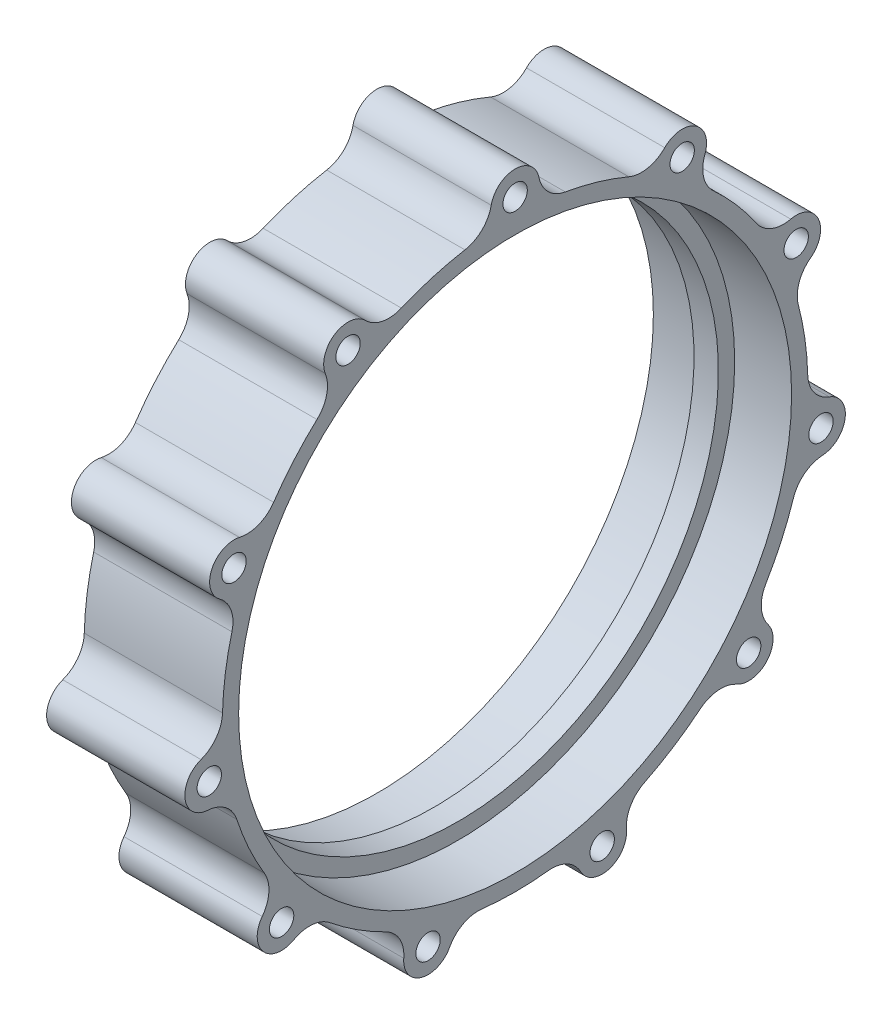
SolidWorks part; units mm, degrees
material "6061 合金"
ref_plane "前视基准面" through (0, 0, 0) normal (0, 0, 1) x (1, 0, 0)
ref_plane "上视基准面" through (0, 0, 0) normal (0, 1, 0) x (1, 0, 0)
ref_plane "右视基准面" through (0, 0, 0) normal (1, 0, 0) x (0, 0, -1)
sketch "草图1" plane through (0, 0, 0) normal (0, 1, 0) x (1, 0, 0)
  line L0 (0, 0) -> (24.0184, 0) construction
  line L1 (0, 34) -> (7, 34)
  line L2 (7, 34) -> (7, 32)
  line L3 (7, 32) -> (10, 32)
  line L4 (10, 32) -> (10, 34)
  line L5 (10, 34) -> (17, 34)
  line L6 (17, 34) -> (17, 36)
  line L7 (17, 36) -> (0, 36)
  line L8 (0, 36) -> (0, 34)
  dimension "D1" = 3
  dimension "D2" = 2
  dimension "D3" = 7
  dimension "D4" = 34
  dimension "D5" = 2
revolve "旋转1" add sketch "草图1" angle 360 about L0
sketch "草图2" plane through (17, 0, 0) normal (1, 0, 0) x (0, 0, -1)
  line L0 (0, 0) -> (0, 38) construction
  arc A1 (2.1754, 35.9342) -> (-2.1754, 35.9342) centre (0, 38) ccw
  circle A2 centre (0, 0) radius 36 construction
  arc A3 (2.1754, 35.9342) -> (-2.1754, 35.9342) centre (0, 0) ccw
  arc A4 (21.2576, 29.0537) -> (17.5974, 31.4059) centre (0, 0) ccw
  arc A5 (21.2576, 29.0537) -> (17.5974, 31.4059) centre (20.5444, 31.9676) ccw
  arc A7 (33.5906, 12.9488) -> (31.7832, 16.9065) centre (0, 0) ccw
  arc A8 (33.5906, 12.9488) -> (31.7832, 16.9065) centre (34.566, 15.7858) ccw
  arc A10 (35.2589, -7.2673) -> (35.878, -2.9607) centre (0, 0) ccw
  arc A11 (35.2589, -7.2673) -> (35.878, -2.9607) centre (37.6132, -5.408) ccw
  arc A13 (25.7327, -25.176) -> (28.5819, -21.8878) centre (0, 0) ccw
  arc A14 (25.7327, -25.176) -> (28.5819, -21.8878) centre (28.7185, -24.8847) ccw
  arc A16 (8.0365, -35.0915) -> (12.2112, -33.8657) centre (0, 0) ccw
  arc A17 (8.0365, -35.0915) -> (12.2112, -33.8657) centre (10.7058, -36.4607) ccw
  arc A18 (-12.2112, -33.8657) -> (-8.0365, -35.0915) centre (0, 0) ccw
  arc A19 (-12.2112, -33.8657) -> (-8.0365, -35.0915) centre (-10.7058, -36.4607) ccw
  arc A20 (-28.5819, -21.8878) -> (-25.7327, -25.176) centre (0, 0) ccw
  arc A21 (-28.5819, -21.8878) -> (-25.7327, -25.176) centre (-28.7185, -24.8847) ccw
  arc A22 (-35.878, -2.9607) -> (-35.2589, -7.2673) centre (0, 0) ccw
  arc A23 (-35.878, -2.9607) -> (-35.2589, -7.2673) centre (-37.6132, -5.408) ccw
  arc A24 (-31.7832, 16.9065) -> (-33.5906, 12.9488) centre (0, 0) ccw
  arc A25 (-31.7832, 16.9065) -> (-33.5906, 12.9488) centre (-34.566, 15.7858) ccw
  arc A26 (-17.5974, 31.4059) -> (-21.2576, 29.0537) centre (0, 0) ccw
  arc A27 (-17.5974, 31.4059) -> (-21.2576, 29.0537) centre (-20.5444, 31.9676) ccw
  point P30 (0, 0)
  dimension "D3" = 6
  dimension "D2" = 38
  dimension "D4" = 11
extrude "凸台-拉伸1" add sketch "草图2" against normal up to surface (17 mm away) up to face at (0, 0, 34)
fillet "圆角1" radius 4 22 edges at (8.5, 35.9342, 2.1754) (8.5, 35.9342, -2.1754) (8.5, -33.8657, -12.2112) (8.5, -35.0915, -8.0365) (8.5, -21.8878, -28.5819) (8.5, -25.176, -25.7327) (8.5, -2.9607, -35.878) (8.5, -7.2673, -35.2589) (8.5, 16.9065, -31.7832) (8.5, 12.9488, -33.5906) (8.5, 31.4059, -17.5974) (8.5, 29.0537, -21.2576) (8.5, 29.0537, 21.2576) (8.5, 31.4059, 17.5974) (8.5, 12.9488, 33.5906) (8.5, 16.9065, 31.7832) (8.5, -7.2673, 35.2589) (8.5, -2.9607, 35.878) (8.5, -25.176, 25.7327) (8.5, -21.8878, 28.5819) (8.5, -35.0915, 8.0365) (8.5, -33.8657, 12.2112)
sketch "草图3" plane through (0, 0, 0) normal (-1, 0, 0) x (0, 0, 1)
  line L0 (0, 36.5) -> (0, 34) construction
  circle A0 centre (0, 38) radius 1.5
  circle A1 centre (-10.7058, -36.4607) radius 1.5
  circle A2 centre (0, 0) radius 34 construction
  circle A3 centre (0, 0) radius 34 construction
  circle A4 centre (0, 0) radius 34 construction
  circle A5 centre (20.5444, 31.9676) radius 1.5
  circle A6 centre (34.566, 15.7858) radius 1.5
  circle A7 centre (37.6132, -5.408) radius 1.5
  circle A8 centre (28.7185, -24.8847) radius 1.5
  circle A9 centre (10.7058, -36.4607) radius 1.5
  circle A10 centre (-28.7185, -24.8847) radius 1.5
  circle A11 centre (-37.6132, -5.408) radius 1.5
  circle A12 centre (-34.566, 15.7858) radius 1.5
  circle A13 centre (-20.5444, 31.9676) radius 1.5
  circle A14 centre (0, 0) radius 41 construction
  arc A15 (2.9387, 38.6034) -> (-2.9387, 38.6034) centre (0, 38) ccw construction
  point P23 (0, 0)
  dimension "D1" = 3
  dimension "D2" = 11
extrude "切除-拉伸1" cut sketch "草图3" against normal through all and the other way through all
ref_plane "基准面1" through (8.5, 0, 0) normal (-1, 0, 0) x (0, 0, 1)
